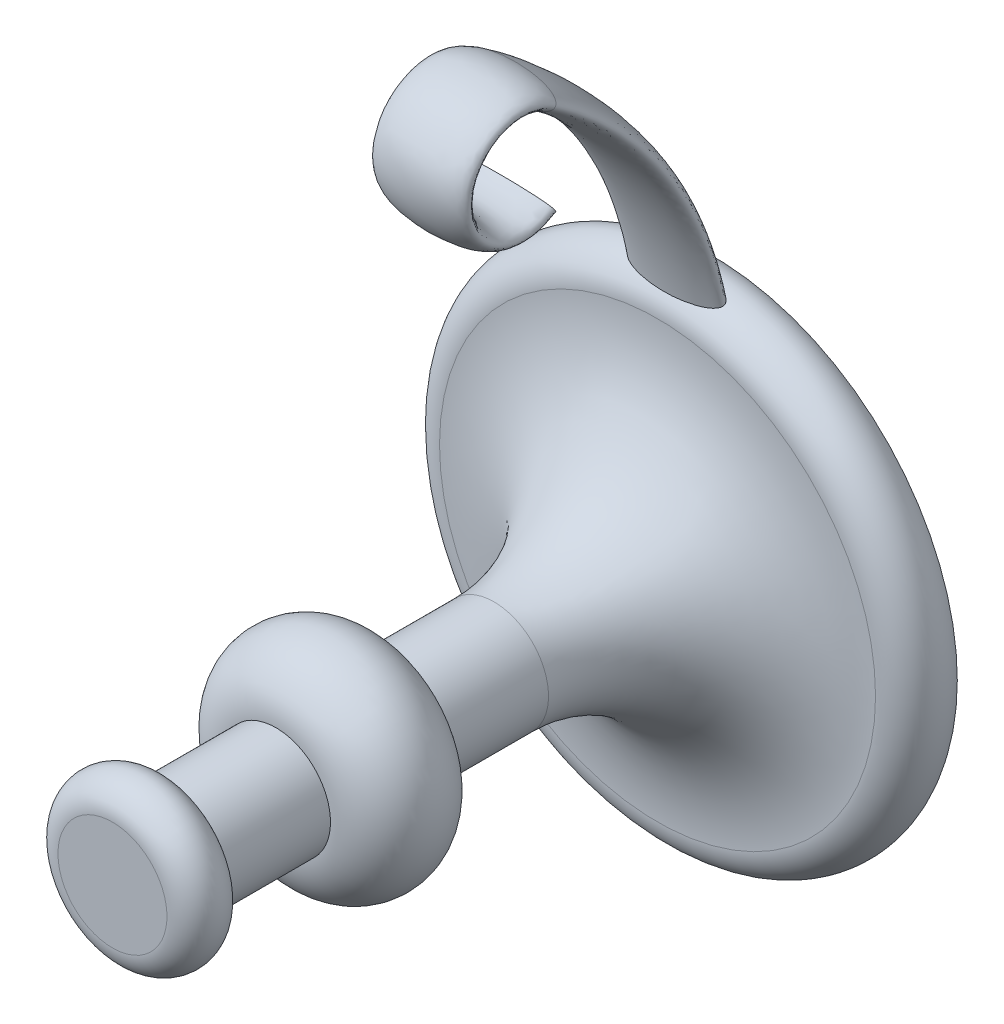
SolidWorks part; units mm, degrees
ref_plane "Ebene vorne" through (0, 0, 0) normal (1, 0, 0) x (0, 1, 0)
ref_plane "Ebene oben" through (0, 0, 0) normal (0, 0, 1) x (0, 1, 0)
ref_plane "Ebene rechts" through (0, 0, 0) normal (0, 1, 0) x (-1, 0, 0)
sketch "Skizze1" plane through (0, 0, 0) normal (1, 0, 0) x (0, 1, 0)
  line L0 (0, 0) -> (0, 220)
  line L1 (0, 220) -> (20, 220)
  line L2 (0, 0) -> (90, 0)
  line L3 (20, 200) -> (20, 160)
  line L4 (20, 120) -> (20, 80)
  arc A0 (20, 220) -> (20, 200) centre (20, 210) cw
  arc A1 (20, 160) -> (20, 120) centre (20, 140) cw
  arc A2 (20, 80) -> (80, 20) centre (80, 80) ccw
  arc A3 (80, 20) -> (90, 0) centre (80, 7.5) cw
  dimension "D4" = 10
  dimension "D5" = 20
  dimension "D7" = 60
  dimension "D8" = 12.5
  dimension "D1" = 220
  dimension "D2" = 20
  dimension "D3" = 90
  dimension "D6" = 40
  dimension "D9" = 80
revolve "Rotation1" add sketch "Skizze1" angle 360 about L0
sketch "Skizze2" plane through (0, 0, 0) normal (1, 0, 0) x (0, 1, 0)
  line L0 (0, 10) -> (60, 10)
  line L1 (0, 227.4356) -> (0, 175.1288) construction
  line L2 (0, 200) -> (0, 160) construction
  line L4 (-90, 0) -> (90, 0) construction
  arc A0 (60, 10) -> (183.5921, 75) centre (60, 160) ccw
  arc A1 (183.5921, 75) -> (150.6342, 75) centre (167.1131, 86.3333) ccw
  point P10 (0, 0)
  dimension "D2" = 150
  dimension "D3" = 65
  dimension "D4" = 20
  dimension "D1" = 60
  dimension "D5" = 10
sketch "Skizze4" plane through (0, 0, 0) normal (0, 1, 0) x (-1, 0, 0)
  ellipse E0 centre (0, 10) end of major axis (17.5, 10) minor radius 5
  dimension "D1" = 10
  dimension "D2" = 35
sweep "Austragung1" add profiles "Skizze4" path "Skizze2"
